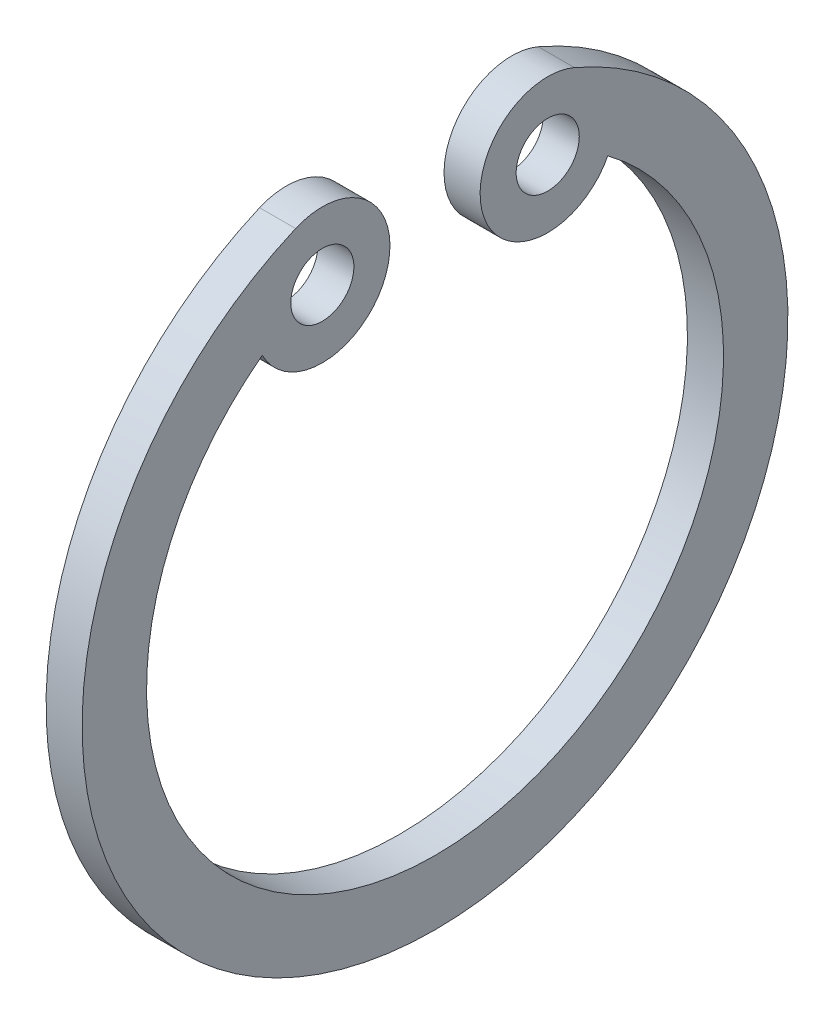
SolidWorks part; units mm, degrees
material "F10 (CK45)"
ref_plane "Front Plane" through (0, 0, 0) normal (0, 0, 1) x (1, 0, 0)
ref_plane "Top Plane" through (0, 0, 0) normal (0, 1, 0) x (1, 0, 0)
ref_plane "Right Plane" through (0, 0, 0) normal (1, 0, 0) x (0, 0, -1)
sketch "Sketch1" plane through (0, 0, 0) normal (1, 0, 0) x (0, 0, -1)
  line L0 (0.1355, 20.6474) -> (0.1355, -19.2922) construction
  circle A0 centre (2.6355, 11.2312) radius 0.7
  arc A1 (3.228, 12.6092) -> (3.9681, 10.5426) centre (2.6355, 11.2312) ccw
  arc A3 (3.9681, 10.5426) -> (-3.6971, 10.5426) centre (0.1355, 5.417) cw
  circle A4 centre (-2.3645, 11.2312) radius 0.7
  arc A5 (-2.957, 12.6092) -> (-3.6971, 10.5426) centre (-2.3645, 11.2312) cw
  arc A6 (-2.957, 12.6092) -> (3.228, 12.6092) centre (0.1355, 5.417) ccw
  dimension "D1" = 1.5
  dimension "D2" = 1.4
  dimension "D3" = 2.5
extrude "Boss-Extrude1" add sketch "Sketch1" along normal blind 0.8
